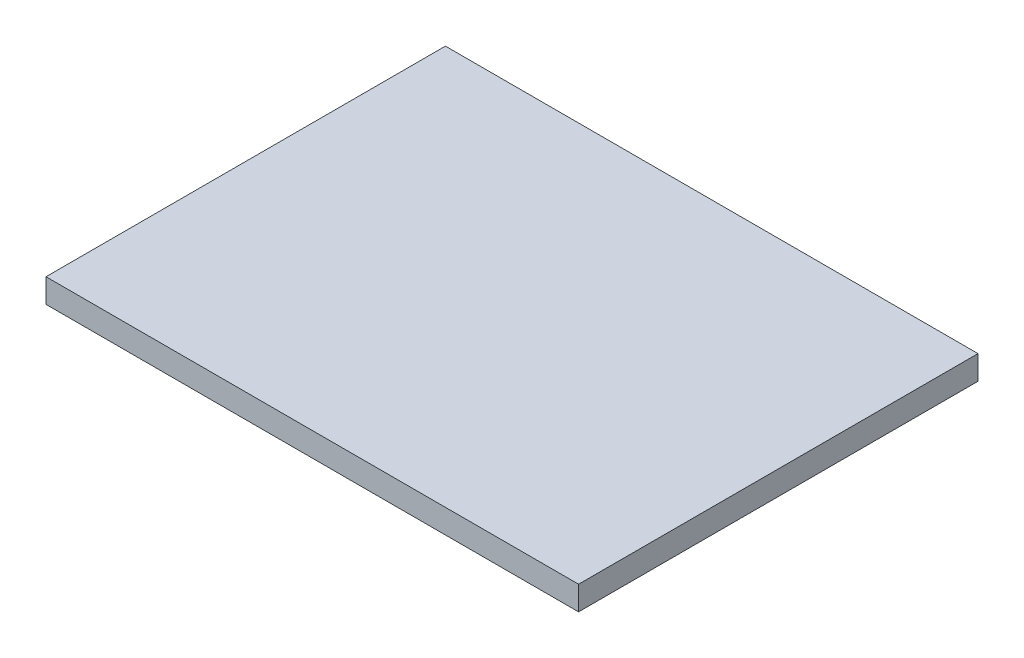
SolidWorks part; units mm, degrees
ref_plane "Front Plane" through (0, 0, 0) normal (0, 0, 1) x (1, 0, 0)
ref_plane "Top Plane" through (0, 0, 0) normal (0, 1, 0) x (1, 0, 0)
ref_plane "Right Plane" through (0, 0, 0) normal (1, 0, 0) x (0, 0, -1)
sketch "Sketch2" plane through (0, 0, 0) normal (0, 1, 0) x (1, 0, 0)
  line L1 (0, 0) -> (400, 0)
  line L2 (0, 0) -> (0, 300)
  line L3 (0, 300) -> (400, 300)
  line L4 (400, 0) -> (400, 300)
  dimension "D1" = 400
  dimension "D2" = 300
extrude "Boss-Extrude1" add sketch "Sketch2" along normal blind 18
